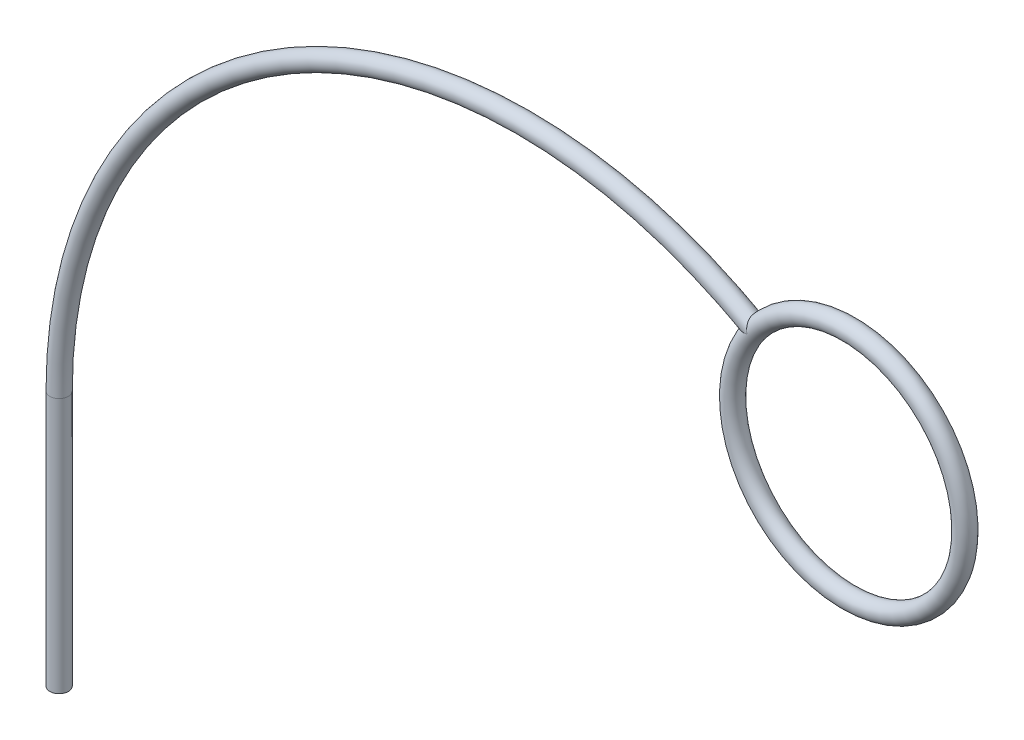
SolidWorks part; units mm, degrees
ref_plane "Front Plane" through (0, 0, 0) normal (0, 0, 1) x (1, 0, 0)
ref_plane "Top Plane" through (0, 0, 0) normal (0, 1, 0) x (1, 0, 0)
ref_plane "Right Plane" through (0, 0, 0) normal (1, 0, 0) x (0, 0, -1)
sketch "Sketch1" plane through (0, 0, 0) normal (0, 0, 1) x (1, 0, 0)
  line L0 (-1.7184, -7.3753) -> (-1.7184, 3.6247)
  line L1 (-1.7184, 3.6247) -> (28.2816, 3.6247) construction
  arc A0 (-1.7184, 3.6247) -> (28.2816, 20.9452) centre (18.2816, 3.6247) cw
  circle A1 centre (32.2652, 17.9235) radius 5
  dimension "D3" = 20
  dimension "D4" = 10
  dimension "D1" = 11
  dimension "D2" = 30
ref_plane "Plane1" through (-1.7184, -7.3753, 0) normal (0, 1, 0) x (1, 0, 0)
sketch "Sketch2" plane through (-1.7184, -7.3753, 0) normal (0, 1, 0) x (1, 0, 0)
  circle A0 centre (0, 0) radius 0.4
  dimension "D1" = 0.8
ref_plane "Plane2" through (28.2816, 20.9452, 0) normal (-0.6043, -0.7967, 0) x (-0.7967, 0.6043, 0)
sketch "Sketch3" plane through (28.2816, 20.9452, 0) normal (-0.6043, -0.7967, 0) x (-0.7967, 0.6043, 0)
  circle A0 centre (0, 0) radius 0.4
  dimension "D1" = 0.8
ref_plane "Plane3" through (0, 0, 0) normal (0, 0, 1) x (1, 0, 0)
sketch "Sketch4" plane through (0, 0, 0) normal (0, 0, 1) x (1, 0, 0)
  circle A0 centre (32.2652, 17.9235) radius 5
sweep "Sweep4" add profiles "Sketch2" path "Sketch1"
sweep "Sweep5" add profiles "Sketch3" path "Sketch4"
